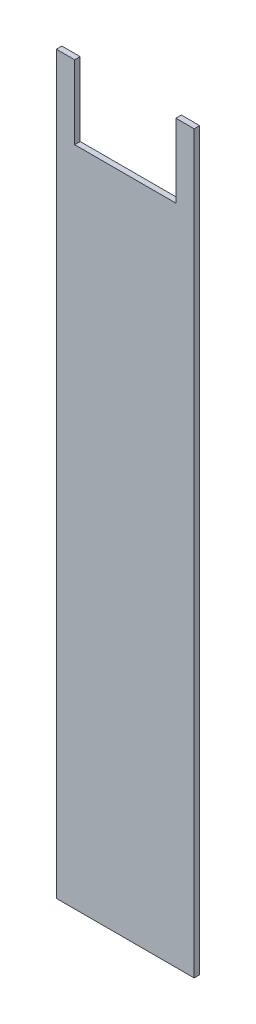
SolidWorks part; units mm, degrees
ref_plane "Přední rovina" through (0, 0, 0) normal (0, 0, 1) x (1, 0, 0)
ref_plane "Horní rovina" through (0, 0, 0) normal (0, 1, 0) x (1, 0, 0)
ref_plane "Pravá rovina" through (0, 0, 0) normal (1, 0, 0) x (0, 0, -1)
sketch "Skica1" plane through (0, 0, 0) normal (0, 0, 1) x (1, 0, 0)
  line L0 (0, 0) -> (0, 400)
  line L1 (0, 400) -> (10, 400)
  line L2 (10, 400) -> (10, 360)
  line L3 (10, 360) -> (65, 360)
  line L4 (65, 360) -> (65, 400)
  line L5 (65, 400) -> (75, 400)
  line L6 (75, 400) -> (75, 0)
  line L7 (75, 0) -> (0, 0)
  dimension "D1" = 75
  dimension "D2" = 400
  dimension "D3" = 10
  dimension "D4" = 40
extrude "Přidat vysunutím1" add sketch "Skica1" along normal blind 3
